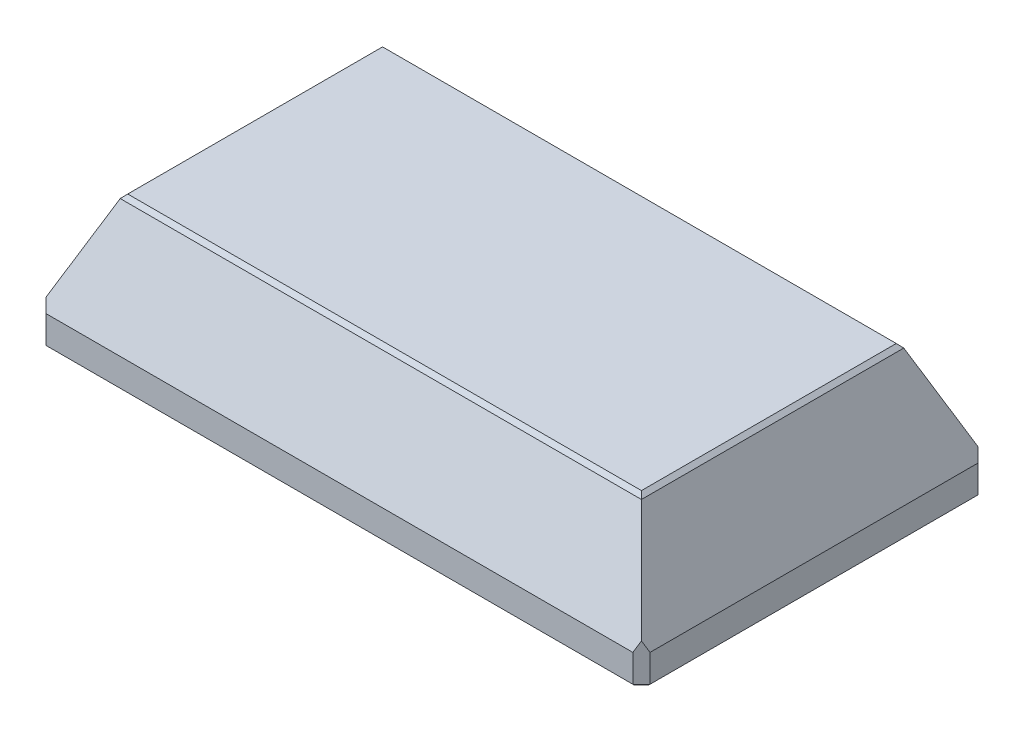
SolidWorks part; units mm, degrees
ref_plane "Front Plane" through (0, 0, 0) normal (0, 0, 1) x (1, 0, 0)
ref_plane "Top Plane" through (0, 0, 0) normal (0, 1, 0) x (1, 0, 0)
ref_plane "Right Plane" through (0, 0, 0) normal (1, 0, 0) x (0, 0, -1)
sketch "Sketch1" plane through (0, 0, 0) normal (0, 1, 0) x (1, 0, 0)
  line L1 (-70, -40) -> (70, -40)
  line L2 (-70, -40) -> (-70, 40)
  line L3 (-70, 40) -> (70, 40)
  line L4 (70, -40) -> (70, 40)
  line L5 (-70, -40) -> (70, 40) construction
  line L6 (-70, 40) -> (70, -40) construction
  point P0 (0, 0)
  dimension "D1" = 140
  dimension "D2" = 80
ref_plane "Plane1" through (0, 30, 0) normal (0, 1, 0) x (1, 0, 0)
sketch "Sketch2" plane through (0, 30, 0) normal (0, 1, 0) x (1, 0, 0)
  line L1 (-60, -30) -> (60, -30)
  line L2 (-60, -30) -> (-60, 30)
  line L3 (-60, 30) -> (60, 30)
  line L4 (60, -30) -> (60, 30)
  line L5 (-60, -30) -> (60, 30) construction
  line L6 (-60, 30) -> (60, -30) construction
  point P0 (0, 0)
  dimension "D1" = 60
  dimension "D2" = 120
extrude "Boss-Extrude1" add sketch "Sketch1" along normal blind 7
sketch "Sketch3" plane through (0, 7, 0) normal (0, 1, 0) x (1, 0, 0)
  line L4 (70, -40) -> (70, 40)
  line L5 (70, 40) -> (-70, 40)
  line L6 (-70, 40) -> (-70, -40)
  line L7 (-70, -40) -> (70, -40)
  line L8 (70, -40) -> (70, 40)
  line L9 (70, 40) -> (-70, 40)
  line L10 (-70, 40) -> (-70, -40)
  line L11 (-70, -40) -> (70, -40)
  dimension "D1" = 0
loft "Loft2" add profiles "Sketch3", "Sketch2"
chamfer "Chamfer1" distance 2 angle 45 4 edges at (-70, 3.5, 40) (70, 3.5, 40) (70, 3.5, -40) (-70, 3.5, -40)
sketch "Sketch4" plane through (0, 0, 0) normal (0, -1, 0) x (1, 0, 0)
  line L0 (0, 40) -> (0, -40) construction
  line L1 (-68, 40) -> (68, 40) construction
  line L2 (68, -40) -> (-68, -40) construction
  line L3 (-40, -36.5) -> (40, -36.5) construction
  circle A0 centre (40, -36.5) radius 2.05
  circle A1 centre (-40, -36.5) radius 2.05
  point P9 (0, -36.5)
  dimension "D3" = 4.1
  dimension "D1" = 3.5
  dimension "D2" = 80
extrude "Cut-Extrude1" cut sketch "Sketch4" against normal blind 7
sketch "Sketch5" plane through (0, 0, 0) normal (0, -1, 0) x (1, 0, 0)
  line L1 (-57, -25) -> (57, -25)
  line L2 (-57, -25) -> (-57, 25)
  line L3 (-57, 25) -> (57, 25)
  line L4 (57, -25) -> (57, 25)
  line L5 (-57, -25) -> (57, 25) construction
  line L6 (-57, 25) -> (57, -25) construction
  point P0 (0, 0)
  dimension "D1" = 50
  dimension "D2" = 114
extrude "Cut-Extrude2" cut sketch "Sketch5" against normal offset from surface (29 mm away) 1 up to face at (0, 30, 0)
mirror "Mirror1" about plane through (0, 0, 0) normal (0, 0, 1) of "Cut-Extrude1"
sketch "Sketch6" plane through (0, 0, 0) normal (0, -1, 0) x (1, 0, 0)
  line L0 (57, 25) -> (57, -25) construction
  line L1 (-57, -31) -> (57, -31)
  line L2 (-57, -31) -> (-57, 31)
  line L3 (-57, 31) -> (57, 31)
  line L4 (57, -31) -> (57, 31)
  line L5 (-57, -31) -> (57, 31) construction
  line L6 (-57, 31) -> (57, -31) construction
  line L7 (57, 25) -> (-57, 25) construction
  point P0 (0, 0)
  dimension "D1" = 6
extrude "Cut-Extrude3" cut sketch "Sketch6" against normal offset from surface (25 mm away) 4 up to face at (0, 29, 0)
sketch "Sketch7" plane through (0, 0, 0) normal (0, -1, 0) x (1, 0, 0)
  line L0 (-57, -31) -> (57, -31) construction
  line L1 (-57, 31) -> (-63, 31)
  line L2 (-57, 31) -> (-57, -31)
  line L3 (-57, -31) -> (-63, -31)
  line L4 (-63, 31) -> (-63, -31)
  line L5 (0, 40) -> (0, -40) construction
  line L6 (-68, 40) -> (68, 40) construction
  line L7 (68, -40) -> (-68, -40) construction
  line L8 (63, 31) -> (63, -31)
  line L9 (57, -31) -> (63, -31)
  line L10 (57, 31) -> (57, -31)
  line L11 (57, 31) -> (63, 31)
  dimension "D1" = 6
extrude "Cut-Extrude4" cut sketch "Sketch7" against normal blind 4
sketch "Sketch8" plane through (0, 4, 0) normal (0, -1, 0) x (1, 0, 0)
  line L0 (-63, 0) -> (63, 0) construction
  line L1 (-63, 31) -> (-63, -31) construction
  line L2 (63, -31) -> (63, 31) construction
  line L3 (-60, -25) -> (-60, 25) construction
  line L4 (-63, 31) -> (-57, -31) construction
  line L5 (0, 31) -> (0, -31) construction
  line L6 (-57, 31) -> (57, 31) construction
  line L7 (-63, -31) -> (63, -31) construction
  circle A0 centre (-60, 25) radius 2.05
  circle A1 centre (-60, -25) radius 2.05
  circle A2 centre (60, -25) radius 2.05
  circle A3 centre (60, 25) radius 2.05
  point P9 (-60, 0)
  dimension "D1" = 4.1
  dimension "D2" = 50
extrude "Cut-Extrude5" cut sketch "Sketch8" against normal blind 6
chamfer "Chamfer2" distance 1 angle 20 4 edges
chamfer "Chamfer3" distance 0.6 angle 45 8 edges at (69, 0, -39) (70, 0, 0) (69, 0, 39) (0, 0, -40) (-69, 0, -39) (-70, 0, 0) (-69, 0, 39) (0, 0, 40)
